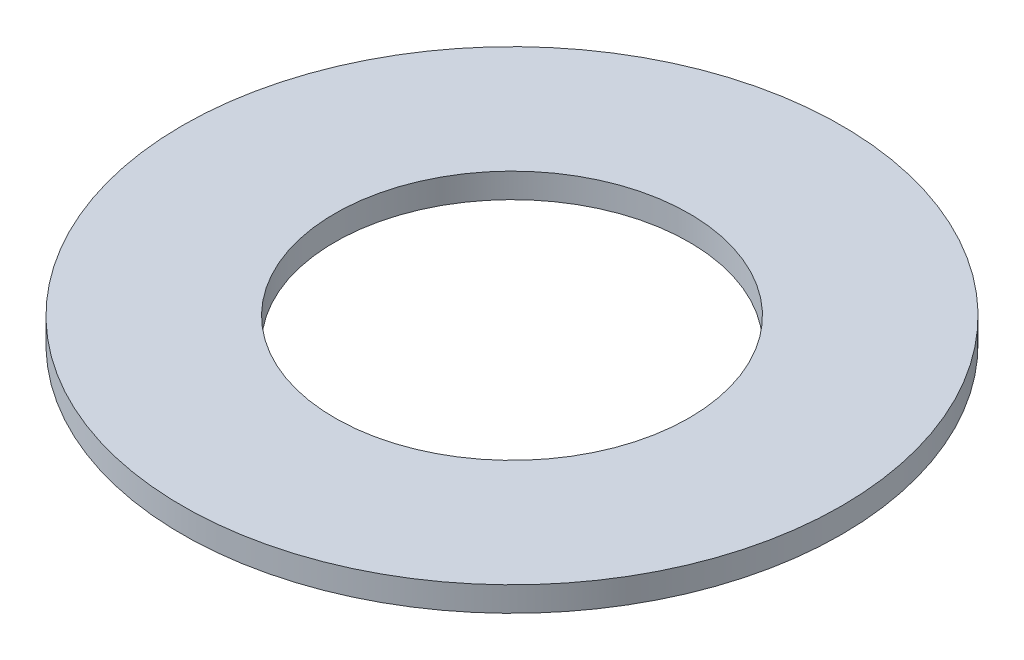
SolidWorks part; units mm, degrees
material "尼龙 6/10"
ref_plane "前视基准面" through (0, 0, 0) normal (0, 0, 1) x (1, 0, 0)
ref_plane "上视基准面" through (0, 0, 0) normal (0, 1, 0) x (1, 0, 0)
ref_plane "右视基准面" through (0, 0, 0) normal (1, 0, 0) x (0, 0, -1)
sketch "草图1" plane through (0, 0, 0) normal (0, 0, 1) x (1, 0, 0)
  line L0 (0, 0) -> (0, 7795.5041) construction
  line L2 (2.15, 0) -> (4, 0)
  line L3 (2.15, 0) -> (2.15, 0.3)
  line L4 (2.15, 0.3) -> (4, 0.3)
  line L5 (4, 0) -> (4, 0.3)
  dimension "D1" = 4.3
  dimension "D2" = 8
  dimension "t" = 0.3
revolve "旋转1" add sketch "草图1" angle 360 about L0
